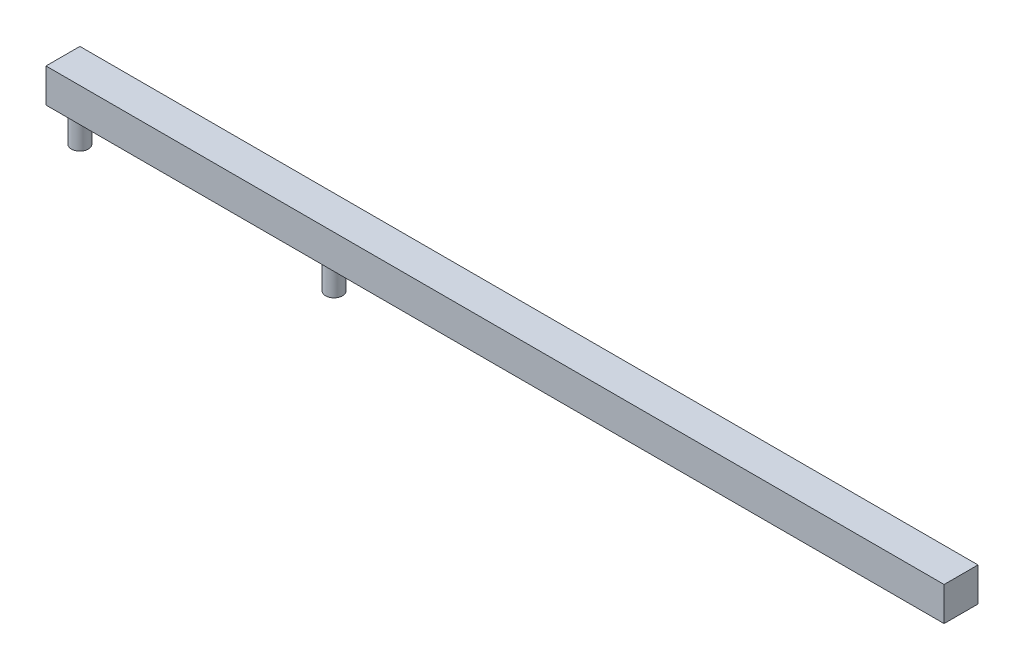
SolidWorks part; units mm, degrees
ref_plane "Plan de face" through (0, 0, 0) normal (0, 0, 1) x (1, 0, 0)
ref_plane "Plan de dessus" through (0, 0, 0) normal (0, 1, 0) x (1, 0, 0)
ref_plane "Plan de droite" through (0, 0, 0) normal (1, 0, 0) x (0, 0, -1)
sketch "Esquisse1" plane through (0, 0, 0) normal (0, 1, 0) x (1, 0, 0)
  line L1 (0, 0) -> (-265, 0)
  line L2 (0, 0) -> (0, -10)
  line L3 (0, -10) -> (-265, -10)
  line L4 (-265, 0) -> (-265, -10)
  dimension "D1" = 265
  dimension "D2" = 10
extrude "Boss.-Extru.1" add sketch "Esquisse1" along normal blind 10
sketch "Esquisse2" plane through (0, 0, 0) normal (0, -1, 0) x (-1, 0, 0)
  line L0 (265, -5) -> (0, -5) construction
  line L1 (265, 0) -> (265, -10) construction
  line L2 (0, -10) -> (0, 0) construction
  circle A0 centre (260, -5) radius 2.5
  circle A1 centre (185, -5) radius 2.5
  dimension "D1" = 5
  dimension "D4" = 5
  dimension "D2" = 5
  dimension "D3" = 75
extrude "Boss.-Extru.2" add sketch "Esquisse2" along normal blind 10
sketch "Esquisse3" plane through (0, 0, 0) normal (0, -1, 0) x (-1, 0, 0)
  line L0 (0, -5) -> (44.3523, -5) construction
  line L1 (0, -10) -> (0, 0) construction
  circle A0 centre (5, -5) radius 2.5
  dimension "D1" = 5
  dimension "D2" = 5
